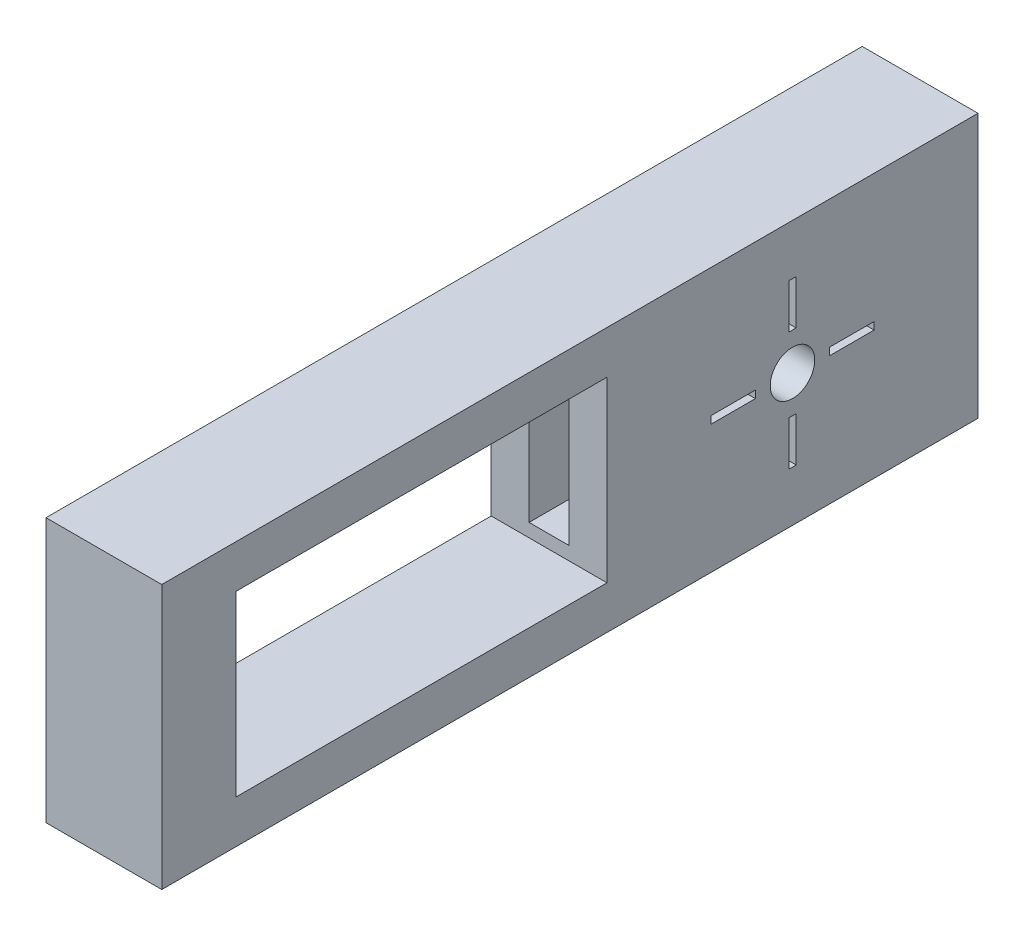
SolidWorks part; units mm, degrees
ref_plane "Front Plane" through (0, 0, 0) normal (1, 0, 0) x (0, 1, 0)
ref_plane "Top Plane" through (0, 0, 0) normal (0, 0, 1) x (0, 1, 0)
ref_plane "Right Plane" through (0, 0, 0) normal (0, 1, 0) x (-1, 0, 0)
sketch "Sketch1" plane through (0, 0, 0) normal (1, 0, 0) x (0, 1, 0)
  line L1 (8.9, -12.5) -> (-8.9, -12.5)
  line L2 (8.9, -12.5) -> (8.9, 12.5)
  line L3 (8.9, 12.5) -> (-8.9, 12.5)
  line L4 (-8.9, -12.5) -> (-8.9, 12.5)
  line L5 (8.9, -12.5) -> (-8.9, 12.5) construction
  line L6 (8.9, 12.5) -> (-8.9, -12.5) construction
  circle A0 centre (0, 0) radius 1.5
  point P0 (0, 0)
  dimension "D3" = 3
  dimension "D1" = 17.8
  dimension "D2" = 25
extrude "Boss-Extrude1" add sketch "Sketch1" along normal mid plane 7.8
ref_plane "Plane2" through (3.9, 0, 0) normal (1, 0, 0) x (0, 0, -1)
sketch "Sketch3" plane through (3.9, 0, 0) normal (1, 0, 0) x (0, 0, -1)
  line L0 (0, 6.4027) -> (0, -6.2592) construction
  line L1 (-6.3453, 0) -> (7.465, 0) construction
  line L3 (-0.25, 5.5) -> (0.25, 5.5)
  line L4 (-0.25, 5.5) -> (-0.25, 2.5)
  line L5 (-0.25, 2.5) -> (0.25, 2.5)
  line L6 (0.25, 5.5) -> (0.25, 2.5)
  line L7 (-0.25, 5.5) -> (0.25, 2.5) construction
  line L8 (-0.25, 2.5) -> (0.25, 5.5) construction
  point P5 (0, 4)
  dimension "D1" = 0.5
  dimension "D2" = 3
  dimension "D3" = 4
extrude "Cut-Extrude1" cut sketch "Sketch3" against normal blind 10
pattern_circular "CirPattern1" count 4 over 360 about axis through (0, 0, 0) along (1, 0, 0) of "Cut-Extrude1"
ref_plane "Plane3" through (0, 0, 12.5) normal (0, 0, 1) x (1, 0, 0)
sketch "Sketch4" plane through (0, 0, 12.5) normal (0, 0, 1) x (1, 0, 0)
  line L1 (1.35, -5.1) -> (-1.35, -5.1)
  line L2 (1.35, -5.1) -> (1.35, 5.1)
  line L3 (1.35, 5.1) -> (-1.35, 5.1)
  line L4 (-1.35, -5.1) -> (-1.35, 5.1)
  line L5 (1.35, -5.1) -> (-1.35, 5.1) construction
  line L6 (1.35, 5.1) -> (-1.35, -5.1) construction
  point P0 (0, 0)
  dimension "D1" = 2.7
  dimension "D2" = 10.2
extrude "Cut-Extrude2" cut sketch "Sketch4" against normal blind 18
ref_plane "Plane4" through (0, 0, -12.5) normal (0, 0, -1) x (-1, 0, 0)
sketch "Sketch5" plane through (0, 0, -12.5) normal (0, 0, -1) x (-1, 0, 0)
  line L1 (1.4, -4.5) -> (-1.4, -4.5)
  line L2 (1.4, -4.5) -> (1.4, 4.5)
  line L3 (1.4, 4.5) -> (-1.4, 4.5)
  line L4 (-1.4, -4.5) -> (-1.4, 4.5)
  line L5 (1.4, -4.5) -> (-1.4, 4.5) construction
  line L6 (1.4, 4.5) -> (-1.4, -4.5) construction
  point P0 (0, 0)
  dimension "D1" = 2.8
  dimension "D2" = 9
extrude "Cut-Extrude3" cut sketch "Sketch5" against normal blind 10
sketch "Sketch6" plane through (0, 0, 12.5) normal (0, 0, 1) x (1, 0, 0)
  line L0 (3.9, -9.79) -> (3.9, 9.79) construction
  line L1 (-3.9, 8.9) -> (3.9, 8.9)
  line L2 (-3.9, 8.9) -> (-3.9, -8.9)
  line L3 (-3.9, -8.9) -> (3.9, -8.9)
  line L4 (3.9, 8.9) -> (3.9, -8.9)
  dimension "D1" = 17.8
extrude "Boss-Extrude2" add sketch "Sketch6" along normal blind 30
sketch "Sketch7" plane through (3.9, 0, 0) normal (1, 0, 0) x (0, 0, -1)
  line L0 (0, 0) -> (-34.4467, 0) construction
  line L2 (-12.5, -6) -> (-37.5, -6)
  line L3 (-12.5, -6) -> (-12.5, 6)
  line L4 (-12.5, 6) -> (-37.5, 6)
  line L5 (-37.5, -6) -> (-37.5, 6)
  line L6 (-12.5, -6) -> (-37.5, 6) construction
  line L7 (-12.5, 6) -> (-37.5, -6) construction
  point P3 (-25, 0)
  dimension "D1" = 25
  dimension "D2" = 12
  dimension "D3" = 12.5
extrude "Cut-Extrude4" cut sketch "Sketch7" against normal blind 30
